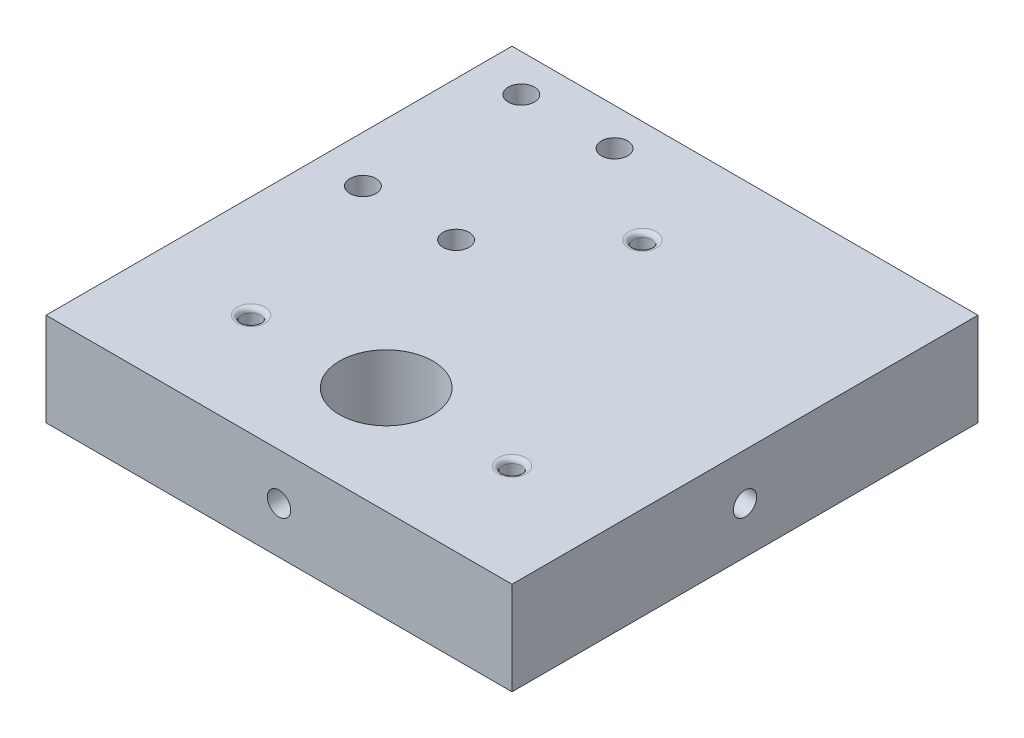
SolidWorks part; units mm, degrees
ref_plane "前视基准面" through (0, 0, 0) normal (0, 0, 1) x (1, 0, 0)
ref_plane "上视基准面" through (0, 0, 0) normal (0, 1, 0) x (1, 0, 0)
ref_plane "右视基准面" through (0, 0, 0) normal (1, 0, 0) x (0, 0, -1)
sketch "草图1" plane through (0, 0, 0) normal (0, 1, 0) x (1, 0, 0)
  line L1 (0, 0) -> (50, 0)
  line L2 (0, 0) -> (0, 50)
  line L3 (0, 50) -> (50, 50)
  line L4 (50, 0) -> (50, 50)
  dimension "D1" = 50
  dimension "D2" = 50
extrude "凸台-拉伸1" add sketch "草图1" along normal blind 10
sketch "草图2" plane through (0, 10, 0) normal (0, 1, 0) x (1, 0, 0)
  line L0 (0, 11) -> (11, 11) construction
  line L1 (0, 50) -> (0, 0) construction
  line L2 (11, 11) -> (11, 0) construction
  line L3 (0, 0) -> (50, 0) construction
  line L4 (50, 11) -> (39, 11) construction
  line L5 (50, 0) -> (50, 50) construction
  line L6 (39, 11) -> (39, 0) construction
  line L7 (25, 39) -> (25, 50) construction
  line L9 (50, 50) -> (0, 50) construction
  circle A0 centre (25, 39) radius 3.25
  circle A1 centre (11, 11) radius 3.25
  circle A2 centre (39, 11) radius 3.25
  dimension "D1" = 6.5
  dimension "D2" = 11
sketch "草图6" plane through (0, 0, 0) normal (0, -1, 0) x (-1, 0, 0)
  line L0 (-25, 11.5) -> (-25, 39) construction
  circle A0 centre (-25, 11.5) radius 10.1
  dimension "D1" = 20.2
  dimension "D2" = 0.5
extrude "切除-拉伸4" cut sketch "草图6" against normal blind 2
sketch "草图7" plane through (0, 2, 0) normal (0, -1, 0) x (-1, 0, 0)
  circle A0 centre (-25, 11.5) radius 5
  dimension "D1" = 10
extrude "切除-拉伸5" cut sketch "草图7" against normal through all
sketch "草图9" plane through (0, 10, 0) normal (0, 1, 0) x (1, 0, 0)
  circle A0 centre (25, 39) radius 1.678
  circle A1 centre (39, 11) radius 1.678
  circle A2 centre (11, 11) radius 1.678
sketch "草图10" plane through (0, 10, 0) normal (0, 1, 0) x (1, 0, 0)
  circle A0 centre (25, 39) radius 1
  circle A1 centre (11, 11) radius 1
  circle A2 centre (39, 11) radius 1
  dimension "D1" = 2
extrude "切除-拉伸6" cut sketch "草图10" against normal blind 2
sketch "草图11" plane through (0, 0, 0) normal (0, -1, 0) x (-1, 0, 0)
  line L0 (-25, 11.5) -> (45399.5226, -20883.7804) construction
  line L1 (-25, 11.5) -> (-45449.5226, -20883.7804) construction
  line L2 (-40, 18.4) -> (-10, 18.4) construction
  line L3 (-10, 18.4) -> (-10, 4.6) construction
  line L4 (-10, 4.6) -> (-40, 4.6) construction
  line L5 (-40, 4.6) -> (-40, 18.4) construction
  circle A0 centre (-40, 18.4) radius 1.25
  circle A1 centre (-40, 4.6) radius 1.25
  circle A2 centre (-10, 18.4) radius 1.25
  circle A3 centre (-10, 4.6) radius 1.25
  dimension "D1" = 2.5
  dimension "D2" = 30
extrude "切除-拉伸7" cut sketch "草图11" against normal blind 8
sketch "草图12" plane through (0, 10, 0) normal (0, 1, 0) x (1, 0, 0)
  line L0 (15, 29) -> (15, 46) construction
  line L1 (15, 46) -> (5, 46) construction
  line L2 (5, 46) -> (5, 29) construction
  line L3 (5, 29) -> (15, 29) construction
  line L4 (50, 50) -> (0, 50) construction
  line L5 (0, 50) -> (0, 0) construction
  circle A0 centre (15, 29) radius 1.4
  circle A1 centre (5, 29) radius 1.4
  circle A2 centre (15, 46) radius 1.4
  circle A3 centre (5, 46) radius 1.4
  dimension "D3" = 2.8
  dimension "D1" = 10
  dimension "D2" = 17
  dimension "D4" = 4
  dimension "D5" = 5
extrude "切除-拉伸8" cut sketch "草图12" against normal blind 5
fillet "圆角1" radius 0.5 3 edges at (25, 10, -38) (11, 10, -10) (39, 10, -10)
sketch "草图13" plane through (0, 0, 0) normal (0, -1, 0) x (-1, 0, 0)
  line L0 (-17.5, 29) -> (-32.5, 29) construction
  line L1 (-32.5, 29) -> (-32.5, 45) construction
  line L2 (-32.5, 45) -> (-17.5, 45) construction
  line L3 (-17.5, 45) -> (-17.5, 29) construction
  line L4 (-25, 45) -> (-25, 50) construction
  line L5 (-50, 50) -> (0, 50) construction
  circle A0 centre (-17.5, 29) radius 1.25
  circle A1 centre (-32.5, 29) radius 1.25
  circle A2 centre (-17.5, 45) radius 1.25
  circle A3 centre (-32.5, 45) radius 1.25
  dimension "D4" = 2.5
  dimension "D1" = 16
  dimension "D2" = 15
  dimension "D3" = 5
extrude "切除-拉伸9" cut sketch "草图13" against normal blind 5
sketch "草图14" plane through (0, 0, 0) normal (-1, 0, 0) x (0, 0, 1)
  line L0 (0, 5) -> (-25.0002, 5) construction
  line L1 (0, 10) -> (0, 0) construction
  line L2 (-25.0002, 5) -> (-25, 10) construction
  line L3 (-50, 10) -> (0, 10) construction
  circle A0 centre (-25.0002, 5) radius 1.25
  dimension "D1" = 2.5
extrude "切除-拉伸11" cut sketch "草图14" against normal blind 6
sketch "草图15" plane through (50, 0, 0) normal (1, 0, 0) x (0, 0, -1)
  circle A0 centre (25.0002, 5) radius 1.25
extrude "切除-拉伸12" cut sketch "草图15" against normal blind 6
sketch "草图16" plane through (0, 0, -50) normal (0, 0, -1) x (-1, 0, 0)
  line L0 (0, 5) -> (-25, 5) construction
  line L1 (0, 10) -> (0, 0) construction
  line L2 (-25, 5) -> (-25, 10) construction
  line L3 (-50, 10) -> (0, 10) construction
  circle A0 centre (-25, 5) radius 1.25
  dimension "D1" = 2.5
extrude "切除-拉伸13" cut sketch "草图16" against normal blind 6
sketch "草图17" plane through (0, 0, 0) normal (0, 0, 1) x (1, 0, 0)
  circle A0 centre (25, 5) radius 1.25
extrude "切除-拉伸14" cut sketch "草图17" against normal blind 6
